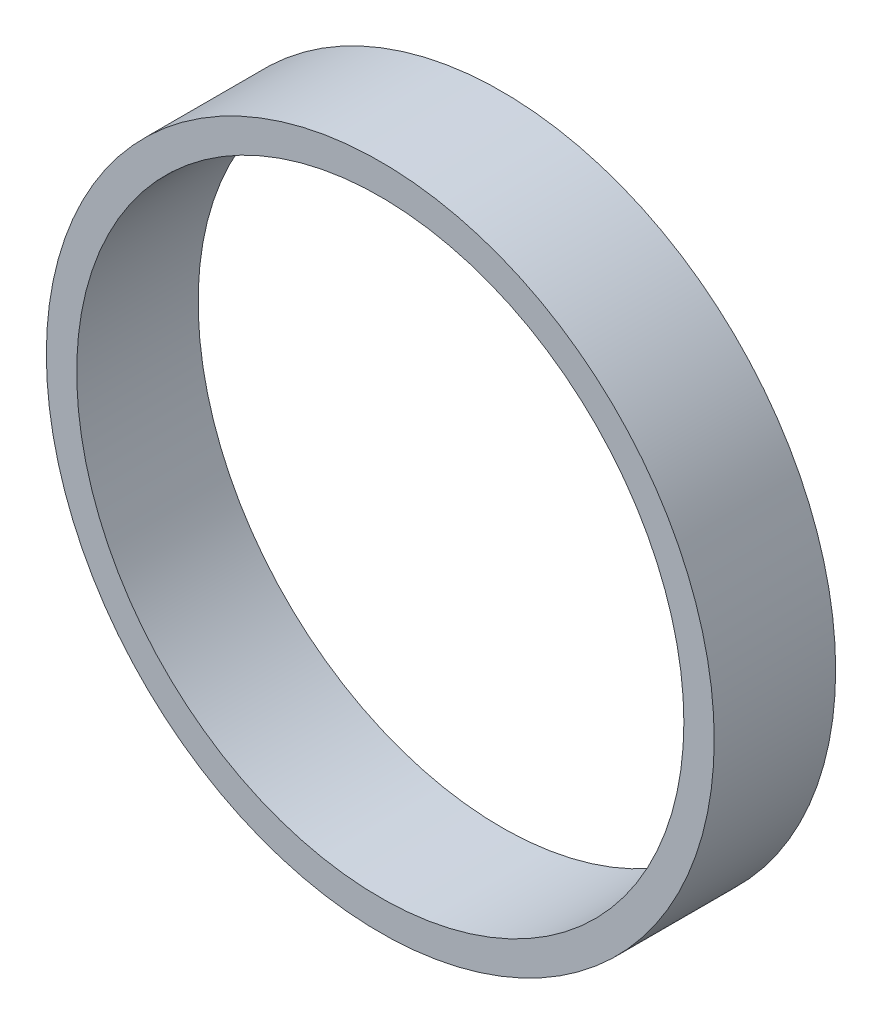
SolidWorks part; units mm, degrees
ref_plane "Vorne" through (0, 0, 0) normal (0, 0, 1) x (1, 0, 0)
ref_plane "Oben" through (0, 0, 0) normal (0, 1, 0) x (1, 0, 0)
ref_plane "Seite" through (0, 0, 0) normal (1, 0, 0) x (0, 0, -1)
sketch "Skizze1" plane through (0, 0, 0) normal (0, 0, 1) x (1, 0, 0)
  circle A0 centre (0, 0) radius 5
  circle A1 centre (0, 0) radius 5.5
  dimension "D1" = 10
  dimension "D2" = 11
extrude "Aufsatz-Linear austragen1" add sketch "Skizze1" along normal blind 2
